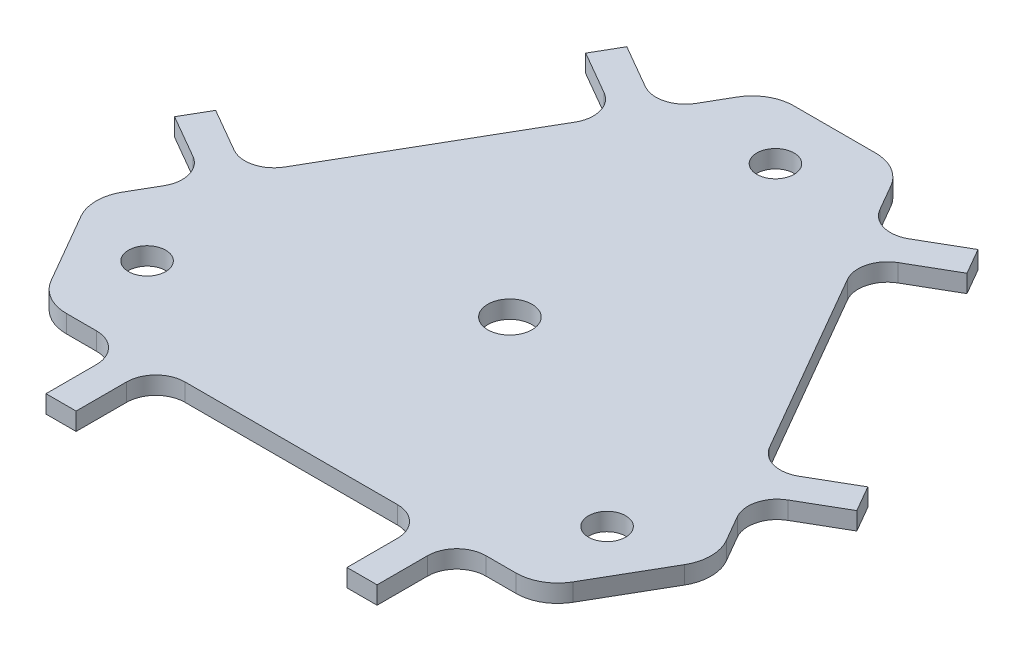
SolidWorks part; units mm, degrees
material "Thornel Mat VMA"
ref_plane "Front Plane" through (0, 0, 0) normal (0, 0, 1) x (1, 0, 0)
ref_plane "Top Plane" through (0, 0, 0) normal (0, 1, 0) x (1, 0, 0)
ref_plane "Right Plane" through (0, 0, 0) normal (1, 0, 0) x (0, 0, -1)
sketch "Sketch1" plane through (0, 0, 0) normal (0, 1, 0) x (1, 0, 0)
  line L0 (49.1829, 65.2758) -> (47.4812, 68.2233) construction
  line L1 (58.5771, 67.0046) -> (53.5542, 64.1046) construction
  line L2 (60.3771, 63.8869) -> (58.5771, 67.0046) construction
  line L3 (55.3542, 60.9869) -> (60.3771, 63.8869) construction
  line L4 (66.1829, 35.831) -> (54.1829, 56.6156) construction
  line L5 (75.5771, 37.5597) -> (70.5542, 34.6597) construction
  line L6 (77.3771, 34.442) -> (75.5771, 37.5597) construction
  line L7 (72.3542, 31.542) -> (77.3771, 34.442) construction
  line L8 (72.8846, 24.2233) -> (71.1829, 27.1707) construction
  line L9 (68.2658, 11.4233) -> (72.8846, 19.4233) construction
  line L10 (60.7055, 9.0233) -> (64.1089, 9.0233) construction
  line L11 (57.5055, 0.0233) -> (57.5055, 5.8233) construction
  line L12 (53.9055, 0.0233) -> (57.5055, 0.0233) construction
  line L13 (53.9055, 5.8233) -> (53.9055, 0.0233) construction
  line L14 (26.7055, 9.0233) -> (50.7055, 9.0233) construction
  line L15 (23.5055, 0.0233) -> (23.5055, 5.8233) construction
  line L16 (19.9055, 0.0233) -> (23.5055, 0.0233) construction
  line L17 (19.9055, 5.8233) -> (19.9055, 0.0233) construction
  line L18 (13.3021, 9.0233) -> (16.7055, 9.0233) construction
  line L19 (4.5263, 19.4233) -> (9.1451, 11.4233) construction
  line L20 (6.228, 27.1707) -> (4.5263, 24.2233) construction
  line L21 (0.0338, 34.442) -> (5.0568, 31.542) construction
  line L22 (1.8338, 37.5597) -> (0.0338, 34.442) construction
  line L23 (6.8568, 34.6597) -> (1.8338, 37.5597) construction
  line L24 (23.228, 56.6156) -> (11.228, 35.831) construction
  line L25 (17.0338, 63.8869) -> (22.0568, 60.9869) construction
  line L26 (18.8338, 67.0046) -> (17.0338, 63.8869) construction
  line L27 (23.8568, 64.1046) -> (18.8338, 67.0046) construction
  line L28 (29.9297, 68.2233) -> (28.228, 65.2758) construction
  line L29 (43.3243, 70.6233) -> (34.0867, 70.6233) construction
  line L30 (0, 0) -> (57.962, 0) construction
  line L31 (0, 0) -> (0, 59.8321) construction
  line L32 (49.0963, 65.2258) -> (47.3946, 68.1733)
  line L33 (43.3243, 70.5233) -> (34.0867, 70.5233)
  line L34 (30.0163, 68.1733) -> (28.3146, 65.2258)
  line L35 (23.8068, 64.018) -> (18.8704, 66.868)
  line L36 (18.8704, 66.868) -> (17.1704, 63.9235)
  line L37 (17.1704, 63.9235) -> (22.1068, 61.0735)
  line L38 (23.3146, 56.5656) -> (11.3146, 35.781)
  line L39 (6.8068, 34.5731) -> (1.8704, 37.4231)
  line L40 (1.8704, 37.4231) -> (0.1704, 34.4786)
  line L41 (0.1704, 34.4786) -> (5.1068, 31.6286)
  line L42 (6.3146, 27.1207) -> (4.6129, 24.1733)
  line L43 (4.6129, 19.4733) -> (9.2317, 11.4733)
  line L44 (13.3021, 9.1233) -> (16.7055, 9.1233)
  line L45 (20.0055, 5.8233) -> (20.0055, 0.1233)
  line L46 (20.0055, 0.1233) -> (23.4055, 0.1233)
  line L47 (23.4055, 0.1233) -> (23.4055, 5.8233)
  line L48 (26.7055, 9.1233) -> (50.7055, 9.1233)
  line L49 (54.0055, 5.8233) -> (54.0055, 0.1233)
  line L50 (54.0055, 0.1233) -> (57.4055, 0.1233)
  line L51 (57.4055, 0.1233) -> (57.4055, 5.8233)
  line L52 (60.7055, 9.1233) -> (64.1089, 9.1233)
  line L53 (68.1792, 11.4733) -> (72.798, 19.4733)
  line L54 (72.798, 24.1733) -> (71.0963, 27.1207)
  line L55 (72.3042, 31.6286) -> (77.2405, 34.4786)
  line L56 (77.2405, 34.4786) -> (75.5405, 37.4231)
  line L57 (75.5405, 37.4231) -> (70.6042, 34.5731)
  line L58 (66.0963, 35.781) -> (54.0963, 56.5656)
  line L59 (55.3042, 61.0735) -> (60.2405, 63.9235)
  line L60 (60.2405, 63.9235) -> (58.5405, 66.868)
  line L61 (58.5405, 66.868) -> (53.6042, 64.018)
  arc A0 (47.4812, 68.2233) -> (43.3243, 70.6233) centre (43.3243, 65.8233) ccw construction
  arc A1 (49.1829, 65.2758) -> (53.5542, 64.1046) centre (51.9542, 66.8758) ccw construction
  arc A2 (55.3542, 60.9869) -> (54.1829, 56.6156) centre (56.9542, 58.2156) ccw construction
  arc A3 (66.1829, 35.831) -> (70.5542, 34.6597) centre (68.9542, 37.431) ccw construction
  arc A4 (72.3542, 31.542) -> (71.1829, 27.1707) centre (73.9542, 28.7707) ccw construction
  arc A5 (72.8846, 19.4233) -> (72.8846, 24.2233) centre (68.7277, 21.8233) ccw construction
  arc A6 (64.1089, 9.0233) -> (68.2658, 11.4233) centre (64.1089, 13.8233) ccw construction
  arc A7 (60.7055, 9.0233) -> (57.5055, 5.8233) centre (60.7055, 5.8233) ccw construction
  arc A8 (53.9055, 5.8233) -> (50.7055, 9.0233) centre (50.7055, 5.8233) ccw construction
  arc A9 (26.7055, 9.0233) -> (23.5055, 5.8233) centre (26.7055, 5.8233) ccw construction
  arc A10 (19.9055, 5.8233) -> (16.7055, 9.0233) centre (16.7055, 5.8233) ccw construction
  arc A11 (9.1451, 11.4233) -> (13.3021, 9.0233) centre (13.3021, 13.8233) ccw construction
  arc A12 (4.5263, 24.2233) -> (4.5263, 19.4233) centre (8.6833, 21.8233) ccw construction
  arc A13 (6.228, 27.1707) -> (5.0568, 31.542) centre (3.4568, 28.7707) ccw construction
  arc A14 (6.8568, 34.6597) -> (11.228, 35.831) centre (8.4568, 37.431) ccw construction
  arc A15 (23.228, 56.6156) -> (22.0568, 60.9869) centre (20.4568, 58.2156) ccw construction
  arc A16 (23.8568, 64.1046) -> (28.228, 65.2758) centre (25.4568, 66.8758) ccw construction
  arc A17 (34.0867, 70.6233) -> (29.9297, 68.2233) centre (34.0867, 65.8233) ccw construction
  arc A18 (47.3946, 68.1733) -> (43.3243, 70.5233) centre (43.3243, 65.8233) ccw
  arc A19 (34.0867, 70.5233) -> (30.0163, 68.1733) centre (34.0867, 65.8233) ccw
  arc A20 (23.8068, 64.018) -> (28.3146, 65.2258) centre (25.4568, 66.8758) ccw
  arc A21 (23.3146, 56.5656) -> (22.1068, 61.0735) centre (20.4568, 58.2156) ccw
  arc A22 (6.8068, 34.5731) -> (11.3146, 35.781) centre (8.4568, 37.431) ccw
  arc A23 (6.3146, 27.1207) -> (5.1068, 31.6286) centre (3.4568, 28.7707) ccw
  arc A24 (4.6129, 24.1733) -> (4.6129, 19.4733) centre (8.6833, 21.8233) ccw
  arc A25 (9.2317, 11.4733) -> (13.3021, 9.1233) centre (13.3021, 13.8233) ccw
  arc A26 (20.0055, 5.8233) -> (16.7055, 9.1233) centre (16.7055, 5.8233) ccw
  arc A27 (26.7055, 9.1233) -> (23.4055, 5.8233) centre (26.7055, 5.8233) ccw
  arc A28 (54.0055, 5.8233) -> (50.7055, 9.1233) centre (50.7055, 5.8233) ccw
  arc A29 (60.7055, 9.1233) -> (57.4055, 5.8233) centre (60.7055, 5.8233) ccw
  arc A30 (64.1089, 9.1233) -> (68.1792, 11.4733) centre (64.1089, 13.8233) ccw
  arc A31 (72.798, 19.4733) -> (72.798, 24.1733) centre (68.7277, 21.8233) ccw
  arc A32 (72.3042, 31.6286) -> (71.0963, 27.1207) centre (73.9542, 28.7707) ccw
  arc A33 (66.0963, 35.781) -> (70.6042, 34.5731) centre (68.9542, 37.431) ccw
  arc A34 (55.3042, 61.0735) -> (54.0963, 56.5656) centre (56.9542, 58.2156) ccw
  arc A35 (49.0963, 65.2258) -> (53.6042, 64.018) centre (51.9542, 66.8758) ccw
  dimension "D1" = 0.1
extrude "Boss-Extrude1" add sketch "Sketch1" along normal blind 2
sketch "Sketch3" plane through (0, 2, 0) normal (0, 1, 0) x (1, 0, 0)
  line L0 (17.3146, 46.1733) -> (38.7055, 33.8233) construction
  line L1 (23.3146, 56.5656) -> (11.3146, 35.781) construction
  line L2 (38.7055, 9.1233) -> (38.7055, 33.8233) construction
  line L4 (26.7055, 9.1233) -> (50.7055, 9.1233) construction
  line L5 (60.0963, 46.1733) -> (38.7055, 33.8233) construction
  line L6 (66.0963, 35.781) -> (54.0963, 56.5656) construction
sketch "Sketch4" plane through (0, 2, 0) normal (0, 1, 0) x (1, 0, 0)
  line L0 (38.7055, 33.8233) -> (38.7055, 63.8233) construction
  line L1 (38.7055, 33.8233) -> (12.7247, 18.8233) construction
  line L2 (38.7055, 33.8233) -> (64.6862, 18.8233) construction
  circle A0 centre (38.7055, 33.8233) radius 30 construction
  circle A1 centre (38.7055, 63.8233) radius 2.1
  circle A2 centre (12.7247, 18.8233) radius 2.1
  circle A3 centre (64.6862, 18.8233) radius 2.1
  dimension "D1" = 60
  dimension "D4" = 4.2
  dimension "D2" = 120
  dimension "D3" = 120
extrude "Cut-Extrude1" cut sketch "Sketch4" against normal through all
sketch "Sketch5" plane through (0, 2, 0) normal (0, 1, 0) x (1, 0, 0)
  circle A0 centre (38.7055, 33.8233) radius 2.5
  dimension "D1" = 5
extrude "Cut-Extrude2" cut sketch "Sketch5" against normal through all
